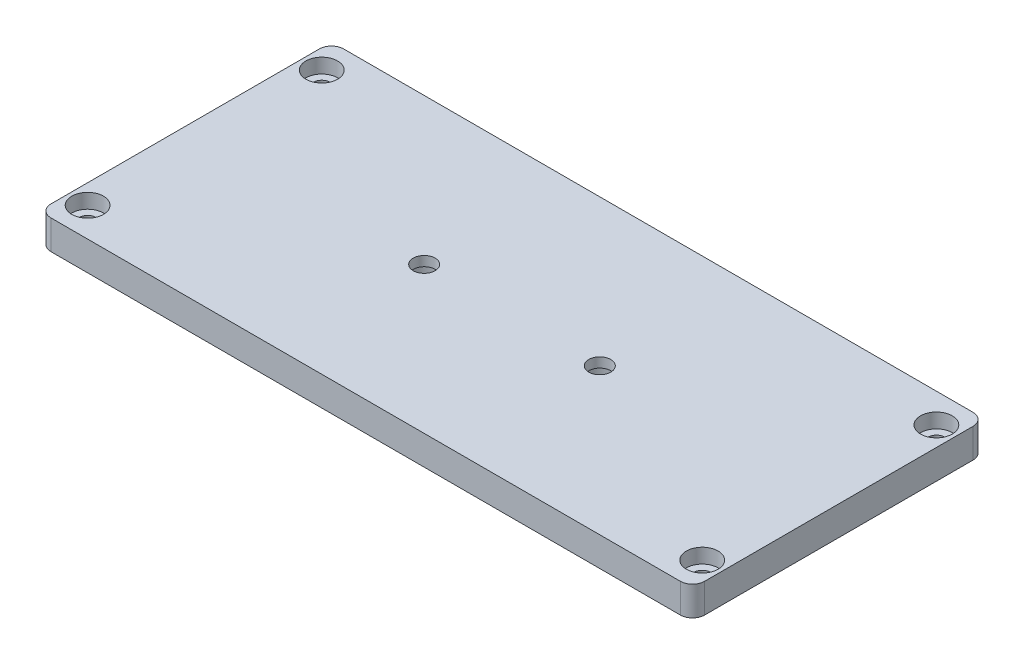
SolidWorks part; units mm, degrees
ref_plane "Front Plane" through (0, 0, 0) normal (0, 0, 1) x (1, 0, 0)
ref_plane "Top Plane" through (0, 0, 0) normal (0, 1, 0) x (1, 0, 0)
ref_plane "Right Plane" through (0, 0, 0) normal (1, 0, 0) x (0, 0, -1)
sketch "Sketch1" plane through (0, 0, 0) normal (0, 1, 0) x (1, 0, 0)
  line L1 (-67, 30) -> (67, 30)
  line L2 (-67, 30) -> (-67, -30)
  line L3 (-67, -30) -> (67, -30)
  line L4 (67, 30) -> (67, -30)
  line L5 (-67, 30) -> (67, -30) construction
  line L6 (-67, -30) -> (67, 30) construction
  point P0 (0, 0)
  dimension "D1" = 60
  dimension "D2" = 134
extrude "Boss-Extrude1" add sketch "Sketch1" along normal blind 6
hole_wizard "CBORE for M3 SHCS1" positions "Sketch2" profile "Sketch3" counterbore size "M3" standard "ANSI Metric"
sketch "Sketch2" plane through (0, 6, 0) normal (0, 1, 0) x (1, 0, 0)
  line L0 (63, 24) -> (63, -24) construction
  line L1 (63, -24) -> (-63, -24) construction
  line L2 (-63, -24) -> (-63, 24) construction
  line L3 (-63, 24) -> (63, 24) construction
  line L6 (-67, -30) -> (67, -30) construction
  line L7 (67, -30) -> (67, 30) construction
  point P0 (-63, 24)
  point P2 (-63, -24)
  point P4 (63, -24)
  point P6 (63, 24)
  point P25 (0, 24)
  point P27 (-63, 0)
  dimension "D1" = 48
  dimension "D2" = 126
sketch "Sketch3" plane through (-63, 6, -24) normal (1, 0, 0) x (0, 0, 1)
  line L0 (0, 0) -> (0, 18.4015)
  line L1 (0, 18.4015) -> (1.7, 17.38)
  line L2 (1.7, 17.38) -> (1.7, 3)
  line L3 (1.7, 3) -> (3.25, 3)
  line L4 (3.25, 3) -> (3.25, 0)
  line L5 (3.25, 0) -> (0, 0)
  line L10 (0, 18.4015) -> (-1.7, 17.38) construction
  line L11 (0, -6.35) -> (0, 107.95) construction
  dimension "Hole Dia." = 3.4
  dimension "Hole Depth" = 17.38
  dimension "C'Bore Dia." = 6.5
  dimension "C'Bore Depth" = 3
  dimension "Drill Angle" = 118
fillet "Fillet1" radius 2.5 4 edges at (67, 3, -30) (67, 3, 30) (-67, 3, 30) (-67, 3, -30)
hole_wizard "CBORE for M4 SHCS1" positions "Sketch5" profile "Sketch6" counterbore size "M4" standard "ANSI Metric"
sketch "Sketch5" plane through (0, 0, 0) normal (0, 1, 0) x (1, 0, 0)
  line L0 (18, 0) -> (-18, 0) construction
  point P0 (-18, 0)
  point P2 (18, 0)
  point P9 (0, 0)
  dimension "D1" = 36
sketch "Sketch6" plane through (-18, 0, 0) normal (1, 0, 0) x (0, 0, -1)
  line L0 (0, 0) -> (0, 13.3519)
  line L1 (0, 13.3519) -> (2.25, 12)
  line L2 (2.25, 12) -> (2.25, 4)
  line L3 (2.25, 4) -> (4, 4)
  line L4 (4, 4) -> (4, 0)
  line L5 (4, 0) -> (0, 0)
  line L10 (0, 13.3519) -> (-2.25, 12) construction
  line L11 (0, -6.35) -> (0, 107.95) construction
  dimension "Hole Dia." = 4.5
  dimension "Hole Depth" = 12
  dimension "C'Bore Dia." = 8
  dimension "C'Bore Depth" = 4
  dimension "Drill Angle" = 118
